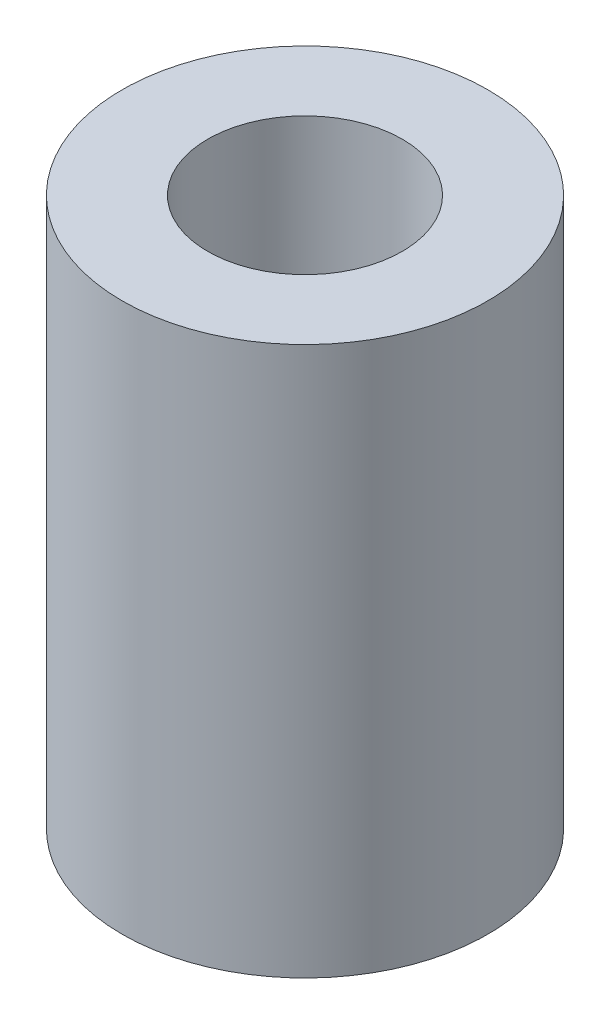
SolidWorks part; units mm, degrees
material "Chrome Stainless Steel"
ref_plane "Front" through (0, 0, 0) normal (0, 0, 1) x (1, 0, 0)
ref_plane "Top" through (0, 0, 0) normal (0, 1, 0) x (1, 0, 0)
ref_plane "Right" through (0, 0, 0) normal (1, 0, 0) x (0, 0, -1)
sketch "Sketch1" plane through (0, 0, 0) normal (0, 1, 0) x (1, 0, 0)
  circle A0 centre (0, 0) radius 6.35
  circle A1 centre (0, 0) radius 3.3782
  dimension "D1" = 6.7564
  dimension "D2" = 12.7
extrude "Extrude1" add sketch "Sketch1" along normal blind 19.05
